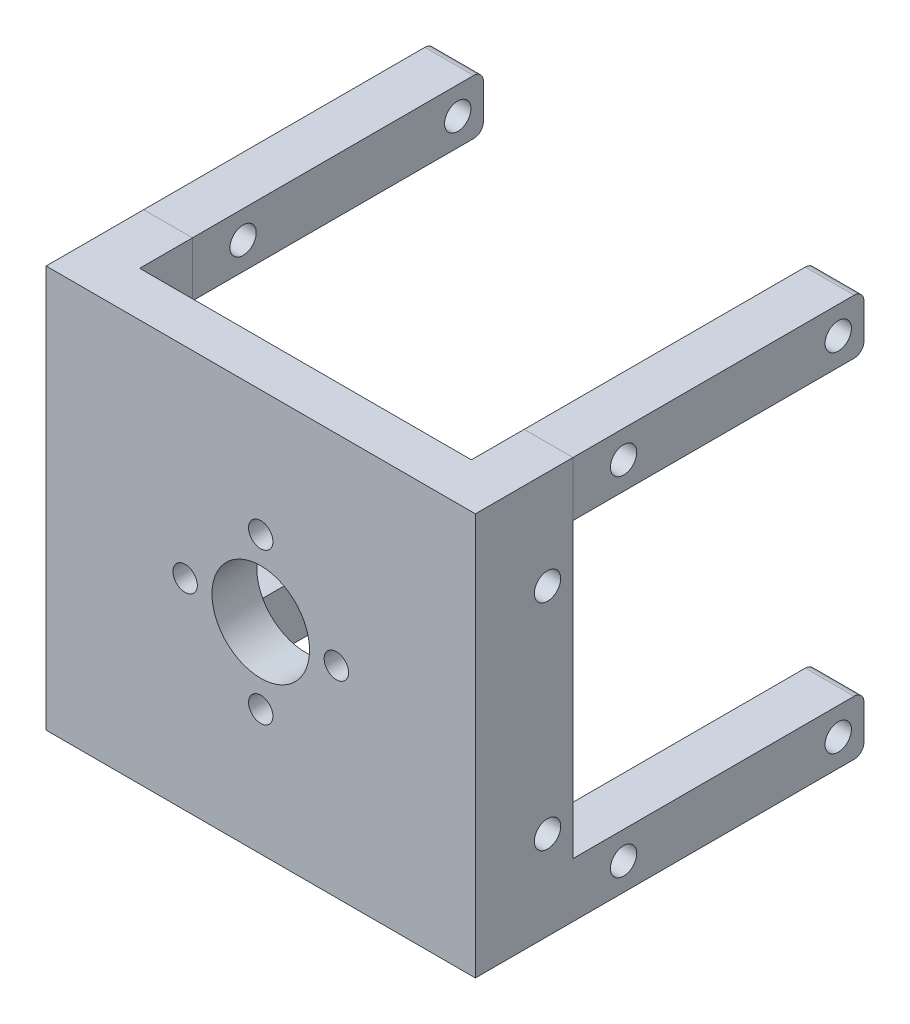
SolidWorks part; units mm, degrees
material "1060 Alloy"
ref_plane "Front Plane" through (0, 0, 0) normal (0, 0, 1) x (1, 0, 0)
ref_plane "Top Plane" through (0, 0, 0) normal (0, 1, 0) x (1, 0, 0)
ref_plane "Right Plane" through (0, 0, 0) normal (1, 0, 0) x (0, 0, -1)
sketch "Sketch1" plane through (0, 0, 0) normal (0, 1, 0) x (1, 0, 0)
  line L1 (-21.5, 2.09) -> (12.5, 2.09)
  line L2 (-26.5, 0.5) -> (-26.5, -0.5)
  line L3 (-26.5, -0.5) -> (17.5, -0.5)
  line L4 (17.5, 0.5) -> (17.5, -0.5)
  line L8 (17.5, 0.5) -> (17.5, 7.5)
  line L9 (17.5, 7.5) -> (12.5, 7.5)
  line L10 (12.5, 2.09) -> (12.5, 7.5)
  line L12 (-26.5, 0.5) -> (-26.5, 7.5)
  line L13 (-26.5, 7.5) -> (-21.5, 7.5)
  line L14 (-21.5, 2.09) -> (-21.5, 7.5)
  point P0 (0, 0)
  dimension "D1" = 34
  dimension "D2" = 1
  dimension "D3" = 5
  dimension "D4" = 5
  dimension "D5" = 7
  dimension "D6" = 7
  dimension "D7" = 2.59
extrude "Boss-Extrude1" add sketch "Sketch1" along normal blind 41.2
sketch "Sketch4" plane through (17.5, 0, 0) normal (1, 0, 0) x (0, 0, -1)
  line L0 (-0.5, 41.2) -> (-0.5, 0) construction
  circle A0 centre (4.89, 31.1) radius 1.35
  circle A1 centre (4.89, 9.1) radius 1.35
  dimension "D3" = 2.7
  dimension "D4" = 2.7
  dimension "D2" = 5.39
  dimension "D1" = 5.39
extrude "Cut-Extrude3" cut sketch "Sketch4" against normal through all
sketch "Sketch6" plane through (0, 41.2, 0) normal (0, 1, 0) x (1, 0, 0)
  line L0 (17.5, -0.5) -> (17.5, 7.5) construction
  line L1 (12.5, 7.5) -> (17.5, 7.5)
  line L2 (12.5, 7.5) -> (12.5, 37.32)
  line L3 (12.5, 37.32) -> (17.5, 37.32)
  line L4 (17.5, 7.5) -> (17.5, 37.32)
  line L5 (-21.5, 2.09) -> (-21.5, 7.5) construction
  line L6 (-26.5, 7.5) -> (-21.5, 7.5)
  line L7 (-26.5, 7.5) -> (-26.5, 37.32)
  line L8 (-26.5, 37.32) -> (-21.5, 37.32)
  line L9 (-21.5, 7.5) -> (-21.5, 37.32)
  dimension "D1" = 0
  dimension "D2" = 29.82
  dimension "D3" = 29.82
  dimension "D4" = 0
extrude "Boss-Extrude2" add sketch "Sketch6" against normal blind 5.6 separate body
sketch "Sketch7" plane through (0, 0, 0) normal (0, -1, 0) x (1, 0, 0)
  line L0 (12.5, -7.5) -> (12.5, -2.09) construction
  line L1 (17.5, -7.5) -> (12.5, -7.5)
  line L2 (17.5, -7.5) -> (17.5, -37.32)
  line L3 (17.5, -37.32) -> (12.5, -37.32)
  line L4 (12.5, -7.5) -> (12.5, -37.32)
  line L5 (-26.5, -7.5) -> (-26.5, 0.5) construction
  line L6 (-21.5, -7.5) -> (-26.5, -7.5)
  line L7 (-21.5, -7.5) -> (-21.5, -37.32)
  line L8 (-21.5, -37.32) -> (-26.5, -37.32)
  line L9 (-26.5, -7.5) -> (-26.5, -37.32)
  dimension "D1" = 29.82
  dimension "D2" = 0
  dimension "D3" = 0
  dimension "D4" = 29.82
extrude "Boss-Extrude3" add sketch "Sketch7" against normal blind 5.6
sketch "Sketch8" plane through (17.5, 0, 0) normal (1, 0, 0) x (0, 0, -1)
  line L1 (-0.5, 0) -> (37.32, 0) construction
  line L2 (7.5, 41.2) -> (37.32, 41.2) construction
  line L3 (7.5, 35.6) -> (37.32, 35.6) construction
  line L4 (-0.5, 41.2) -> (-0.5, 0) construction
  circle A0 centre (34.69, 2.8) radius 1.35
  circle A1 centre (34.69, 38.4) radius 1.35
  circle A2 centre (12.69, 38.4) radius 1.35
  circle A3 centre (12.69, 2.8) radius 1.35
  dimension "D1" = 35.19
  dimension "D2" = 2.7
  dimension "D3" = 2.7
  dimension "D4" = 2.8
  dimension "D5" = 2.8
  dimension "D6" = 2.7
  dimension "D7" = 2.8
  dimension "D8" = 35.19
  dimension "D9" = 2.7
  dimension "D10" = 13.19
  dimension "D11" = 13.19
extrude "Cut-Extrude5" cut sketch "Sketch8" against normal blind 74.6
fillet "Fillet4" radius 1 2 edges at (-24, 35.6, -37.32) (-24, 41.2, -37.32)
fillet "Fillet5" radius 1 2 edges at (15, 35.6, -37.32) (15, 41.2, -37.32)
fillet "Fillet6" radius 1 2 edges at (15, 0, -37.32) (15, 5.6, -37.32)
fillet "Fillet7" radius 1 2 edges at (-24, 0, -37.32) (-24, 5.6, -37.32)
sketch "Sketch10" plane through (0, 0, -2.09) normal (0, 0, -1) x (-1, 0, 0)
  line L0 (-12.5, 41.2) -> (21.5, 41.2) construction
  line L2 (-12.5, 0) -> (21.5, 0) construction
  circle A0 centre (4.5, 20.6) radius 5
  point P4 (4.5, 41.2)
  point P7 (4.5, 0)
  dimension "D1" = 10
  dimension "D3" = 20.6
  dimension "D2" = 0
extrude "Cut-Extrude7" cut sketch "Sketch10" against normal blind 3
sketch "Sketch11" plane through (0, 0, 0.5) normal (0, 0, 1) x (1, 0, 0)
  circle A0 centre (-4.5, 28.35) radius 1.25
  circle A1 centre (-4.5, 20.6) radius 5 construction
  dimension "D1" = 2.5
  dimension "D2" = 7.75
extrude "Cut-Extrude8" cut sketch "Sketch11" against normal blind 4 and the other way blind 3.2
pattern_circular "CirPattern1" count 4 over 360 about axis through (-4.5, 20.6, 0) along (0, 0, 1) of "Cut-Extrude8"
sketch "Sketch12" plane through (0, 0, 0) normal (0, -1, 0) x (1, 0, 0)
  line L1 (17.5, 0.5) -> (-26.5, 0.5)
  line L2 (17.5, 0.5) -> (17.5, 2.5)
  line L3 (17.5, 2.5) -> (-26.5, 2.5)
  line L4 (-26.5, 0.5) -> (-26.5, 2.5)
  dimension "D1" = 2
extrude "Boss-Extrude4" add sketch "Sketch12" against normal blind 41.2
sketch "Sketch13" plane through (0, 0, 2.5) normal (0, 0, 1) x (1, 0, 0)
  circle A0 centre (-4.5, 20.6) radius 5
  circle A1 centre (-4.5, 12.85) radius 1.25
  circle A2 centre (3.25, 20.6) radius 1.25
  circle A3 centre (-4.5, 28.35) radius 1.25
  circle A4 centre (-12.25, 20.6) radius 1.25
extrude "Cut-Extrude9" cut sketch "Sketch13" against normal blind 5.2
